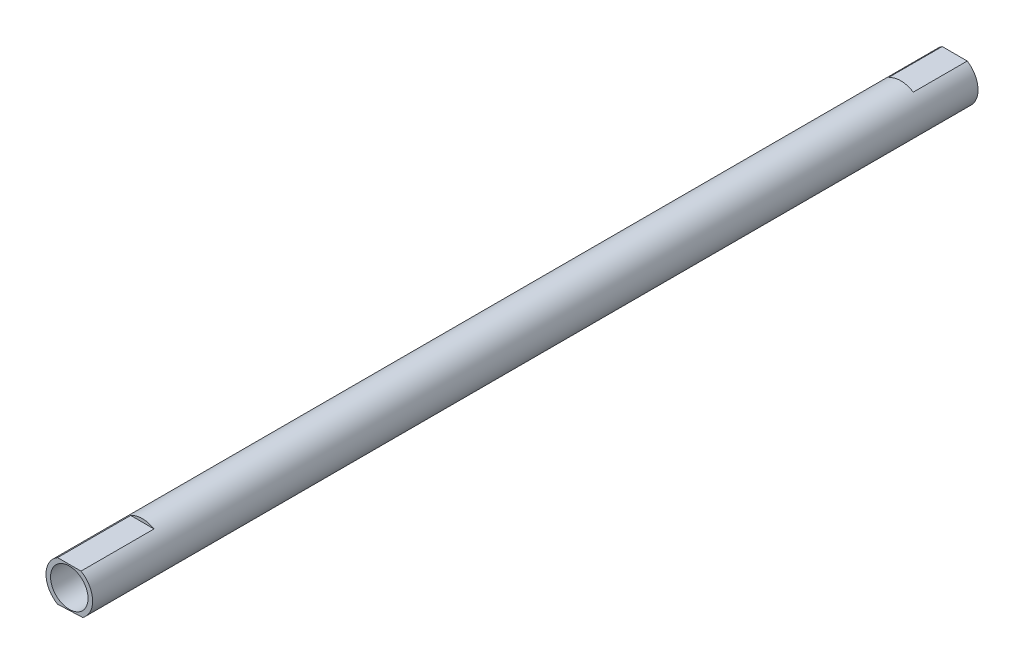
SolidWorks part; units mm, degrees
ref_plane "Front Plane" through (0, 0, 0) normal (0, 0, 1) x (1, 0, 0)
ref_plane "Top Plane" through (0, 0, 0) normal (0, 1, 0) x (1, 0, 0)
ref_plane "Right Plane" through (0, 0, 0) normal (1, 0, 0) x (0, 0, -1)
sketch "Sketch2" plane through (0, 0, 0) normal (0, 0, 1) x (1, 0, 0)
  circle A0 centre (0, 0) radius 13.3836
  circle A1 centre (0, 0) radius 10.7699
extrude "Boss-Extrude1" add sketch "Sketch2" along normal blind 508
sketch "Sketch3" plane through (0, 0, 508) normal (0, 0, 1) x (1, 0, 0)
  line L0 (-6.7074, 11.5815) -> (6.7074, 11.5815)
  line L1 (-6.7074, -11.5815) -> (7.6481, -10.983)
  circle A0 centre (0, 0) radius 13.3836 construction
  arc A1 (-6.7074, 11.5815) -> (6.7074, 11.5815) centre (0, 0) cw
  arc A2 (-6.7074, -11.5815) -> (7.6481, -10.983) centre (0, 0) ccw
  circle M1 centre (0, 0) radius 13.3836
extrude "Cut-Extrude1" cut sketch "Sketch3" against normal blind 41.91 contours L0 M1 | L1 M1
sketch "Sketch4" plane through (0, 0, 0) normal (0, 0, -1) x (-1, 0, 0)
  line L0 (-7.1969, 11.2838) -> (7.1969, 11.2838)
  line L1 (-7.1969, -11.2838) -> (7.8201, -10.8612)
  circle A0 centre (0, 0) radius 13.3836 construction
  arc A1 (-7.1969, 11.2838) -> (7.2591, 11.2439) centre (0, 0) cw
  arc A2 (-7.1969, -11.2838) -> (7.8201, -10.8612) centre (0, 0) ccw
  circle M1 centre (0, 0) radius 13.3836
extrude "Cut-Extrude2" cut sketch "Sketch4" against normal blind 30.988 contours L0 M1 | L1 M1
